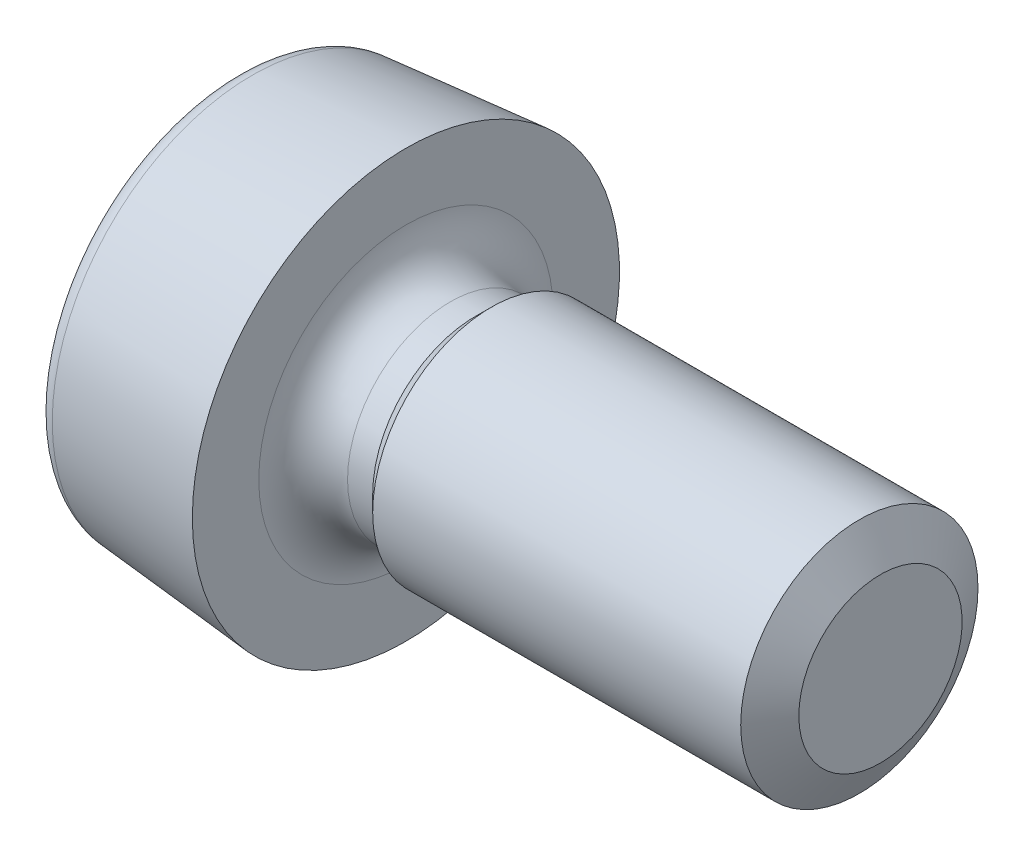
SolidWorks part; units mm, degrees
revolve "基体-旋转" add sketch "草图3" angle 360 about L0
sketch "草图3" plane through (0, 0, 0) normal (0, 0, 1) x (1, 0, 0)
  line L0 (-2.1696, 0) -> (16.014, 0) construction
  line L1 (0, 0) -> (6.8, 0)
  line L2 (6.8, 0) -> (6.8, 1.25)
  line L3 (6.8, 1.25) -> (2.7, 1.25)
  line L4 (2.7, 1.25) -> (2.5325, 1.0825)
  line L5 (2.5325, 1.0825) -> (2.2675, 1.0825)
  line L7 (1.8, 2.25) -> (0.1826, 2.1085)
  line L8 (0, 1.9093) -> (0, 0)
  line L9 (1.8, 1.55) -> (1.8, 2.25)
  arc A0 (1.8, 1.55) -> (2.2675, 1.0825) centre (2.2675, 1.55) ccw
  arc A1 (0.1826, 2.1085) -> (0, 1.9093) centre (0.2, 1.9093) ccw
  dimension "D4" = 0.2
  dimension "D1" = 5
  dimension "dk" = 4.5
  dimension "d" = 2.5
  dimension "D2" = 45
  dimension "da" = 3.1
  dimension "k" = 1.8
  dimension "D3" = 2.165
  dimension "a" = 0.9
  dimension "l" = 5
cosmetic thread "装饰螺纹线1" parameters "D2"=2.165
material "AISI 304"
ref_plane "前视" through (0, 0, 0) normal (0, 0, 1) x (1, 0, 0)
ref_plane "上视" through (0, 0, 0) normal (0, 1, 0) x (1, 0, 0)
ref_plane "右视" through (0, 0, 0) normal (1, 0, 0) x (0, 0, -1)
sketch "尺寸草图" plane through (0, 0, 0) normal (0, 0, 1) x (1, 0, 0)
  line L0 (0, 0) -> (5, 0)
  line L1 (0, 0) -> (0, 4.5)
  line L2 (5, 0) -> (5, 2.5)
  point P5 (0, 3.1)
  point P6 (1.8, 0)
  point P7 (2.7, 0)
  point P8 (4.55, 0)
  point P9 (3.8, 0)
  point P10 (2.3, 0)
  point P11 (0, 0.1)
  dimension "dk" = 4.5
  dimension "d" = 2.5
  dimension "da" = 3.1
  dimension "k" = 1.8
  dimension "a" = 0.9
  dimension "l" = 5
  dimension "P" = 0.45
  dimension "h" = 1.2
  dimension "m" = 2.7
  dimension "r" = 0.1
sketch "草图4" plane through (0, 0, 0) normal (0, 0, 1) x (1, 0, 0)
  line L0 (6.5774, 1.25) -> (7.0274, 1.25)
  line L1 (7.0274, 1.25) -> (6.8, 0.8603)
  line L2 (6.8, 0.8603) -> (6.5774, 1.25)
  line L3 (6.8, 1.25) -> (2.7, 1.25) construction
  line L4 (6.8, -1.25) -> (6.8, 1.25) construction
  line L5 (-0.218, 0) -> (14.7427, 0) construction
  line L6 (-2.1696, 0) -> (16.014, 0) construction
  dimension "D1" = 0.45
  dimension "D2" = 0.3897
  dimension "D3" = 60
revolve "切除-旋转1" cut sketch "草图4" angle 360 about L5
pattern_linear "阵列(线性)1" [suppressed] count 9 spacing 0.45 along (1, 0, 0)
sketch "草图5" plane through (0, 0, 0) normal (-1, 0, 0) x (0, 0, 1)
  line L1 (-0.225, 1.35) -> (0.225, 1.35)
  line L2 (-0.225, 1.35) -> (-0.225, -1.35)
  line L3 (-0.225, -1.35) -> (0.225, -1.35)
  line L4 (0.225, 1.35) -> (0.225, -1.35)
  point P4 (-0.225, 0)
  point P5 (0, 1.35)
  dimension "m" = 2.7
  dimension "D1" = 0.45
ref_plane "基准面1" through (1.2, 0, 0) normal (1, 0, 0) x (0, 0, -1)
sketch "草图6" plane through (1.2, 0, 0) normal (1, 0, 0) x (0, 0, -1)
  point P0 (0, 0)
loft "切除-放样1" cut profiles "草图5", "草图6"
pattern_circular "阵列(圆周)1" count 2 every 90 about axis through (0, 0, 0) along (1, 0, 0) of "切除-放样1"
equation "\"l@草图3\" = \"l@尺寸草图\""
equation "\"dk@草图3\" = \"dk@尺寸草图\""
equation "\"da@草图3\" = \"da@尺寸草图\""
equation "\"D4@草图3\" = \"r@尺寸草图\"*2"
equation "\"k@草图3\" = \"k@尺寸草图\""
equation "\"a@草图3\" = \"a@尺寸草图\""
equation "\"D3@草图3\" = \"d@尺寸草图\"*0.866"
equation "\"d@草图3\" = \"d@尺寸草图\""
equation "\"D2@装饰螺纹线1\" = \"d@尺寸草图\"*0.866"
equation "\"D1@草图4\" = \"P@尺寸草图\""
equation "\"D2@草图4\" = \"P@尺寸草图\"*0.866"
equation "\"D3@阵列(线性)1\" = \"P@尺寸草图\""
equation "\"D1@阵列(线性)1\" = (\"l@尺寸草图\"-\"a@尺寸草图\")/\"P@尺寸草图\""
equation "\"D1@基准面1\" = \"h@尺寸草图\""
equation "\"m@草图5\" = \"m@尺寸草图\""
equation "\"D1@草图5\" = \"P@尺寸草图\""
